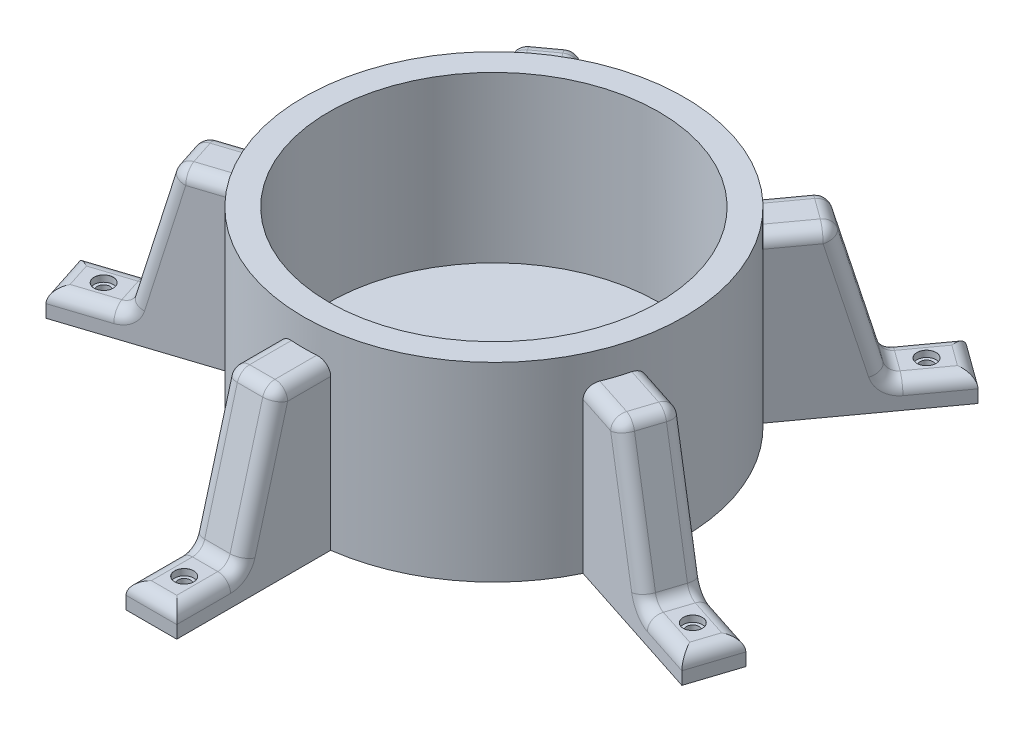
SolidWorks part; units mm, degrees
ref_plane "Alzado" through (0, 0, 0) normal (0, 0, 1) x (1, 0, 0)
ref_plane "Planta" through (0, 0, 0) normal (0, 1, 0) x (1, 0, 0)
ref_plane "Vista lateral" through (0, 0, 0) normal (1, 0, 0) x (0, 0, -1)
sketch "Croquis4" plane through (0, 0, 0) normal (0, 1, 0) x (1, 0, 0)
  circle A0 centre (0, 0) radius 150
  dimension "D1" = 300
extrude "Saliente-Extruir3" add sketch "Croquis4" along normal blind 150
ref_plane "Plano1" through (0, 150, 0) normal (0, 1, 0) x (1, 0, 0)
sketch "Croquis7" plane through (0, 150, 0) normal (0, 1, 0) x (1, 0, 0)
  circle A0 centre (0, 0) radius 130
  dimension "D1" = 260
extrude "Cortar-Extruir1" cut sketch "Croquis7" against normal blind 130
sketch "Croquis8" plane through (0, 0, 0) normal (1, 0, 0) x (0, 0, -1)
  line L5 (-190.2126, 128.7024) -> (-220, 20)
  line L6 (-220, 20) -> (-270, 20)
  line L7 (-270, 20) -> (-270, 0)
  line L9 (-190.2126, 128.7024) -> (-141.5469, 128.7024)
  line L10 (-141.5469, 128.7024) -> (-141.5469, 0)
  line L11 (-141.5469, 0) -> (-270, 0)
  dimension "D1" = 141.5469
  dimension "D2" = 190.2126
  dimension "D3" = 50
  dimension "D4" = 20
  dimension "D5" = 220
  dimension "D6" = 128.7024
extrude "Saliente-Extruir5" add sketch "Croquis8" along normal blind 20 and the other way blind 20
fillet "Redondeo1" radius 10 9 edges at (-20, 74.3512, 205.1063) (20, 74.3512, 205.1063) (-20, 128.7024, 169.4366) (20, 128.7024, 169.4366) (-20, 20, 245) (20, 20, 245) (0, 20, 270) (0, 128.7024, 190.2126) (0, 20, 220)
hole_wizard "Refrentado para tornillo con cabeza plana de M81" positions "Croquis11" profile "Croquis12" counterbore size "M8" standard "ISO" end condition through all
sketch "Croquis11" plane through (0, 20, 0) normal (0, 1, 0) x (1, 0, 0)
  point P0 (0, -244.1206)
sketch "Croquis12" plane through (0, 20, 244.1206) normal (1, 0, 0) x (0, 0, 1)
  line L0 (0, 0) -> (0, 20)
  line L1 (0, 20) -> (5, 20)
  line L3 (5, 20) -> (5, 5)
  line L4 (7.5, 5) -> (5, 5)
  line L5 (7.5, 5) -> (7.5, 0.025)
  line L6 (7.5, 0.025) -> (7.525, 0)
  line L7 (7.525, 0) -> (0, 0)
  line L8 (-7.5, 0.025) -> (-7.525, 0) construction
  line L11 (0, -6.35) -> (0, 107.95) construction
  dimension "Diámetro de taladro hasta el siguiente" = 10
  dimension "Profundidad de taladro hasta el siguiente" = 20
  dimension "Diámetro de refrentado" = 15
  dimension "Profundidad de refrentado" = 5
  dimension "Diámetro de avellanado cercano" = 15.05
  dimension "Ángulo de avellanado cercano" = 90
pattern_circular "MatrizC1" count 5 over 360 about axis through (0, 0, 0) along (0, 1, 0) of "Saliente-Extruir5", "Redondeo1", "Refrentado para tornillo con cabeza plana de M81"
sketch "Croquis13" plane through (0, 0, 0) normal (0, 1, 0) x (1, 0, 0)
  circle A0 centre (0, 0) radius 20
  dimension "D1" = 40
extrude "Cortar-Extruir2" cut sketch "Croquis13" along normal through all
